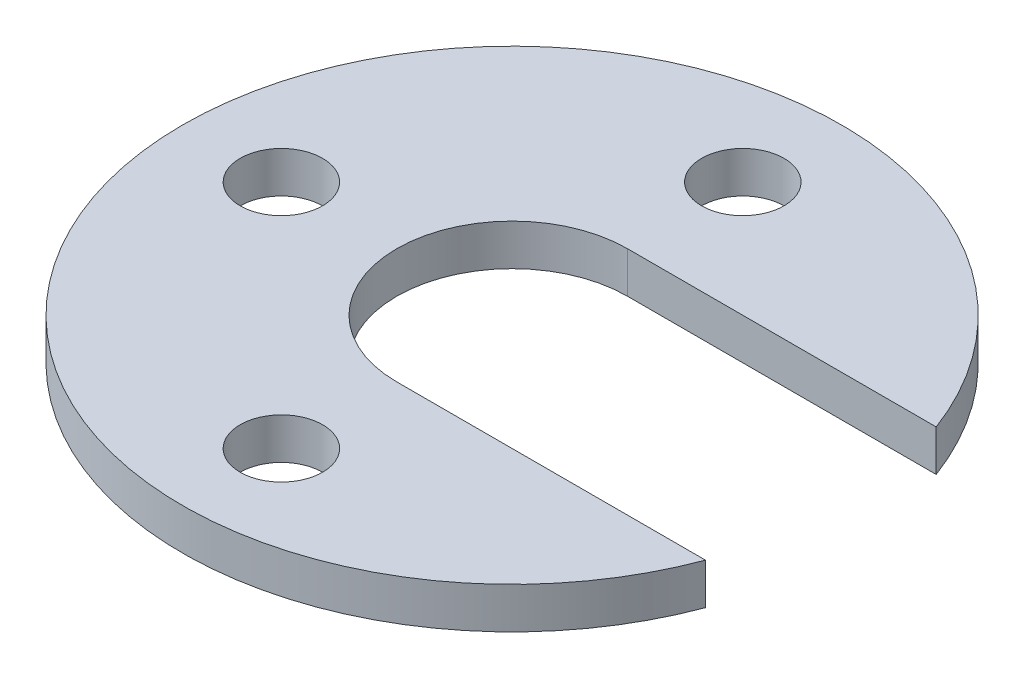
SolidWorks part; units mm, degrees
ref_plane "Front Plane" through (0, 0, 0) normal (0, 0, 1) x (1, 0, 0)
ref_plane "Top Plane" through (0, 0, 0) normal (0, 1, 0) x (1, 0, 0)
ref_plane "Right Plane" through (0, 0, 0) normal (1, 0, 0) x (0, 0, -1)
sketch "Sketch1" plane through (0, 0, 0) normal (0, 1, 0) x (1, 0, 0)
  line L0 (0, 14) -> (37.47, 14)
  line L1 (0, -14) -> (37.47, -14)
  arc A0 (37.47, 14) -> (37.47, -14) centre (0, 0) ccw
  circle A2 centre (0, 28) radius 5
  circle A3 centre (0, -28) radius 5
  circle A4 centre (-28, 0) radius 5
  arc A5 (0, 14) -> (0, -14) centre (0, 0) ccw
  dimension "D1" = 80
  dimension "D5" = 10
  dimension "D6" = 10
  dimension "D7" = 10
  dimension "D2" = 28
  dimension "D3" = 28
  dimension "D4" = 28
  dimension "D8" = 14
extrude "Boss-Extrude1" add sketch "Sketch1" along normal blind 5
